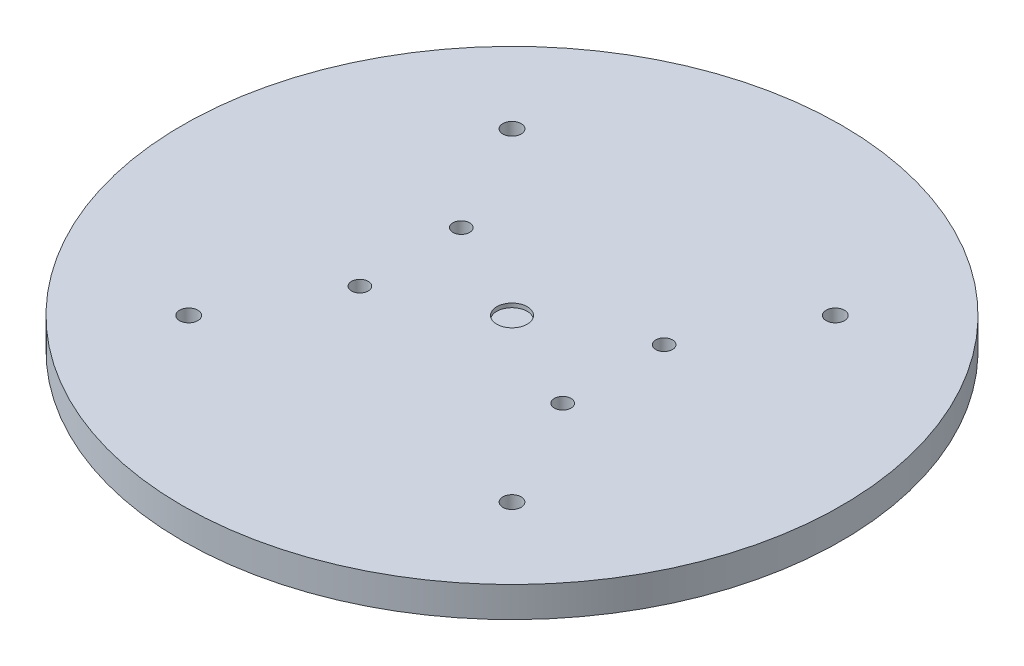
SolidWorks part; units mm, degrees
ref_plane "Front Plane" through (0, 0, 0) normal (0, 0, 1) x (1, 0, 0)
ref_plane "Top Plane" through (0, 0, 0) normal (0, 1, 0) x (1, 0, 0)
ref_plane "Right Plane" through (0, 0, 0) normal (1, 0, 0) x (0, 0, -1)
sketch "Sketch1" plane through (0, 0, 0) normal (0, 1, 0) x (1, 0, 0)
  line L1 (-40.49, -40.49) -> (40.49, -40.49) construction
  line L2 (-40.49, -40.49) -> (-40.49, 40.49) construction
  line L3 (-40.49, 40.49) -> (40.49, 40.49) construction
  line L4 (40.49, -40.49) -> (40.49, 40.49) construction
  line L5 (-40.49, -40.49) -> (40.49, 40.49) construction
  line L6 (-40.49, 40.49) -> (40.49, -40.49) construction
  circle A0 centre (0, 0) radius 82.55
  circle A1 centre (40.49, 40.49) radius 2.286
  circle A2 centre (40.49, -40.49) radius 2.286
  circle A3 centre (-40.49, -40.49) radius 2.286
  circle A4 centre (-40.49, 40.49) radius 2.286
  dimension "D1" = 165.1
  dimension "D3" = 4.572
  dimension "D4" = 4.572
  dimension "D5" = 4.572
  dimension "D6" = 4.572
  dimension "D2" = 80.98
extrude "Boss-Extrude2" add sketch "Sketch1" along normal blind 7.62
sketch "Sketch2" plane through (0, 7.62, 0) normal (0, 1, 0) x (1, 0, 0)
  circle A0 centre (0, 0) radius 3.81
  dimension "D1" = 7.62
extrude "Cut-Extrude1" cut sketch "Sketch2" against normal blind 1.016
sketch "Sketch3" plane through (0, 0, 0) normal (0, -1, 0) x (1, 0, 0)
  line L1 (-25.4, -12.7) -> (25.4, -12.7) construction
  line L2 (-25.4, -12.7) -> (-25.4, 12.7) construction
  line L3 (-25.4, 12.7) -> (25.4, 12.7) construction
  line L4 (25.4, -12.7) -> (25.4, 12.7) construction
  line L5 (-25.4, -12.7) -> (25.4, 12.7) construction
  line L6 (-25.4, 12.7) -> (25.4, -12.7) construction
  circle A0 centre (-25.4, 12.7) radius 2.1
  circle A1 centre (25.4, 12.7) radius 2.1
  circle A2 centre (25.4, -12.7) radius 2.1
  circle A3 centre (-25.4, -12.7) radius 2.1
  point P0 (0, 0)
  dimension "D3" = 4.2
  dimension "D4" = 4.2
  dimension "D5" = 4.2
  dimension "D6" = 4.2
  dimension "D1" = 50.8
  dimension "D2" = 25.4
extrude "Cut-Extrude2" cut sketch "Sketch3" against normal blind 54.356
